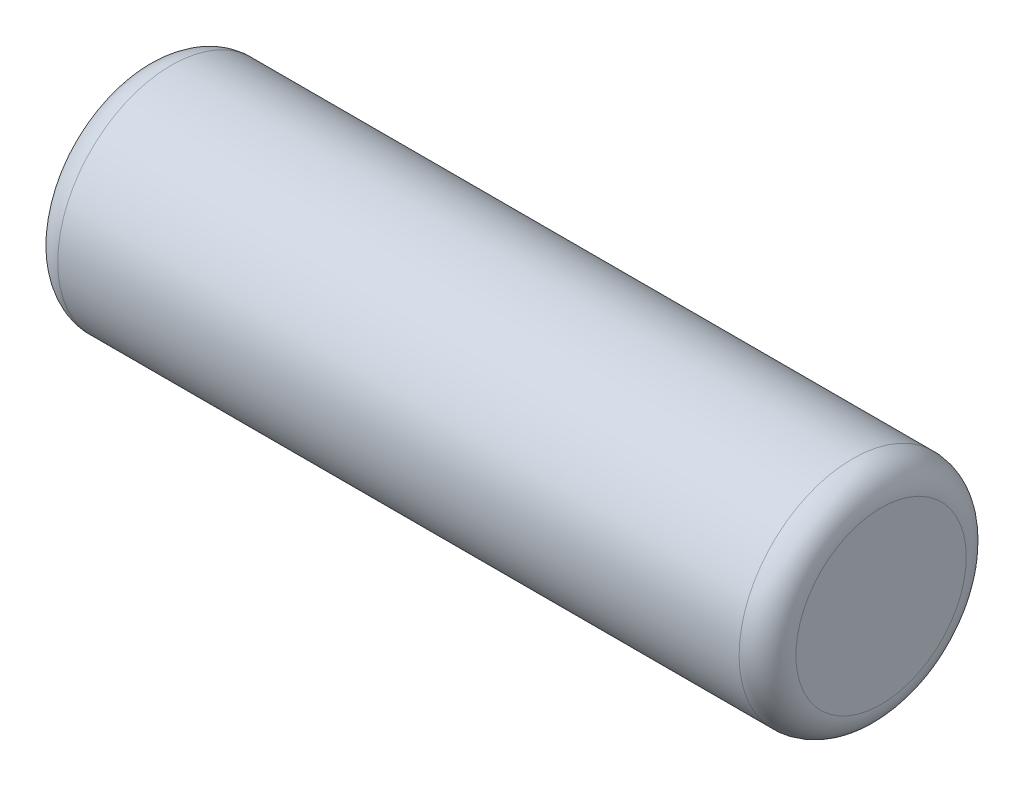
SolidWorks part; units mm, degrees
ref_plane "Спереди" through (0, 0, 0) normal (0, 0, 1) x (1, 0, 0)
ref_plane "Сверху" through (0, 0, 0) normal (0, 1, 0) x (1, 0, 0)
ref_plane "Справа" through (0, 0, 0) normal (1, 0, 0) x (0, 0, -1)
sketch "Эскиз1" plane through (0, 0, 0) normal (1, 0, 0) x (0, 0, -1)
  circle A0 centre (0, 0) radius 8
  dimension "D1" = 16
extrude "Бобышка-Вытянуть1" add sketch "Эскиз1" along normal blind 52
fillet "Скругление2" radius 2 2 edges at (0, 0, -8) (52, 0, -8)
